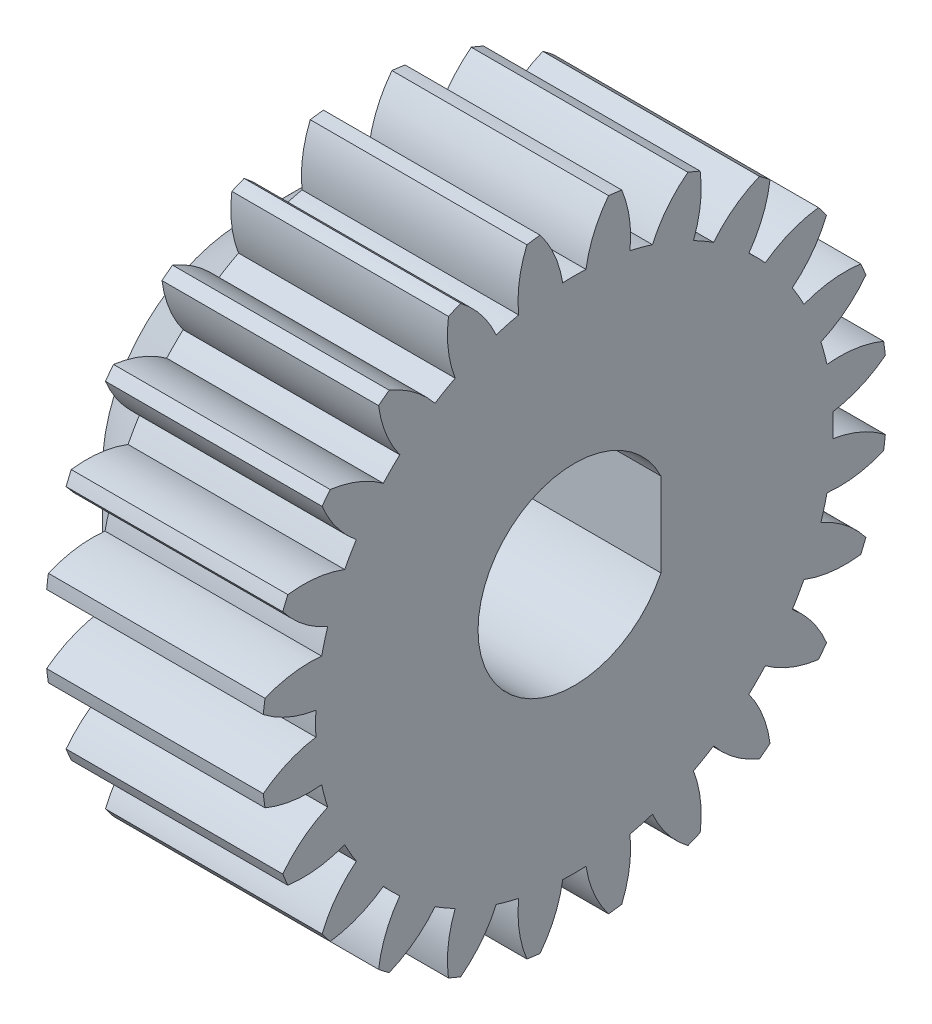
SolidWorks part; units mm, degrees
ref_plane "Plane1" through (0, 0, 0) normal (0, 0, 1) x (1, 0, 0)
ref_plane "Plane2" through (0, 0, 0) normal (0, 1, 0) x (1, 0, 0)
ref_plane "Plane3" through (0, 0, 0) normal (1, 0, 0) x (0, 0, -1)
sketch "HoldingSke" plane through (0, 0, 0) normal (0, 1, 0) x (1, 0, 0)
  line L0 (0, 0) -> (1.8271, -0.8135)
  line L1 (-15, 0) -> (100, 0) construction
  line L2 (0, 0) -> (-2.1039, 2.3779)
  line L3 (0, 0) -> (-11.863, 4.5341)
  line L4 (0, 0) -> (7.8894, 3.5126)
  line L5 (0, 0) -> (-46.8476, -17.4728)
  line L6 (0, 0) -> (-3.7303, -2.5169)
  line L7 (-2.1039, 2.3779) -> (8.6586, 51.2059)
  line L8 (-76.2, 54.61) -> (-75.7, 54.61)
  line L9 (-71.009, 38.7566) -> (-53.1078, 45.2721)
  line L10 (-76.2, 71.12) -> (104.1128, 71.12)
  line L11 (0, 0) -> (-4.5, 0)
  line L12 (-76.2, 101.6) -> (-76.181, 101.6)
  line L13 (24.9733, 27.94) -> (52.9518, 28.4284)
  line L14 (24.9733, 27.94) -> (24.9743, 27.94)
  line L15 (24.9733, 27.94) -> (100.4006, 29.5858)
  line L16 (-63.627, -0.5) -> (-12.827, -0.5)
  circle A0 centre (0, 0) radius 1.5
  circle A1 centre (0, 0) radius 5.374
  circle A2 centre (0, 0) radius 37.5
  circle A3 centre (0, 0) radius 1.5
  dimension "MHD" = 10.748
  dimension "Hub_dia" = 75
  dimension "Bore" = 3
  dimension "MBD" = 3
  dimension "Num_teeth" = 24
  dimension "Pitch" = 2
  dimension "Overall_len" = 50
  dimension "Show_teeth" = 24
  dimension "Thickness" = 4.5
  dimension "OAL" = 50.0001
  dimension "T_dim" = 0.5
  dimension "Ap" = 20
  dimension "H" = 19.05
  dimension "Pitch_radius" = 180.3128
  dimension "Width" = 4.5
  dimension "Backlash" = 0.019
  dimension "Addendum_fac" = 1
  dimension "Dedendum_fac" = 1.25
  dimension "Clearance_fac" = 0.25
  dimension "Dedendum_add" = 0.001
  dimension "Module" = 0.5
sketch "BasProSke" plane through (0, 0, 0) normal (0, 1, 0) x (1, 0, 0)
  line L0 (-10, 0) -> (60, 0) construction
  line L1 (0, 0) -> (0, 6.5)
  line L2 (0, 0) -> (4.5, 0)
  line L3 (4.5, 0) -> (4.5, 6.5)
  line L4 (4.5, 6.5) -> (0, 6.5)
  dimension "Thickness" = 4.5
  dimension "Diameter" = 13
revolve "Base-Revolve" add sketch "BasProSke" angle 360 about L0
sketch "TooCutSke" plane through (0, 0, 0) normal (1, 0, 0) x (0, 0, -1)
  line L1 (0, 0) -> (0, 107) construction
  line L2 (0, 0) -> (-0.4257, 5.9849) construction
  line L3 (0, 0) -> (-1.5635, 11.876) construction
  line L4 (-0.4257, 5.9849) -> (-0.7818, 5.938) construction
  arc A0 (0.2416, 5.3686) -> (-0.2416, 5.3686) centre (0, 0) ccw
  arc A1 (0.7297, 6.4845) -> (-0.7297, 6.4845) centre (0, 0) ccw
  circle A2 centre (0, 0) radius 6 construction
  circle A3 centre (0, 0) radius 5.6382 construction
  arc A4 (-0.2416, 5.3686) -> (-0.7297, 6.4845) centre (-2.6126, 4.9963) ccw
  arc A5 (0.7297, 6.4845) -> (0.2416, 5.3686) centre (2.6126, 4.9963) ccw
  dimension "Root_dia" = 10.748
  dimension "Overcut_dia" = 13.0508
  dimension "Pitch_dia" = 12
  dimension "Base_dia" = 11.2763
  dimension "Flank_rad" = 2.4
  dimension "Half_ang" = 7.5
  dimension "Half_CT" = 0.3592
extrude "ToothCut" cut sketch "TooCutSke" along normal through all
fillet "Breaks" [suppressed] radius 0.01
fillet "RootFillets" [suppressed] radius 0.126
pattern_circular "TeethCuts" count 24 every 15 about axis through (-10, 0, 0) along (1, 0, 0) of "ToothCut", "RootFillets", "Breaks"
sketch "HubNeaOneSke" plane through (0, 0, 0) normal (-1, 0, 0) x (0, 0, 1)
  circle A0 centre (0, 0) radius 5.374
  dimension "Diameter" = 10.748
extrude "HubNearOne" [suppressed] add sketch "HubNeaOneSke" along normal blind 45.5001
sketch "HubNeaBotSke" plane through (0, 0, 0) normal (-1, 0, 0) x (0, 0, 1)
  circle A0 centre (0, 0) radius 5.374
  dimension "Diameter" = 10.748
extrude "HubNearBoth" [suppressed] add sketch "HubNeaBotSke" along normal blind 22.75
ref_plane "FarPln" through (4.5, 0, 0) normal (1, 0, 0) x (0, 0, -1)
sketch "HubFarSke" plane through (4.5, 0, 0) normal (1, 0, 0) x (0, 0, -1)
  circle A0 centre (0, 0) radius 5.374
  dimension "Diameter" = 10.748
extrude "HubFar" [suppressed] add sketch "HubFarSke" along normal blind 22.75
sketch "BorSke" plane through (0, 0, 0) normal (1, 0, 0) x (0, 0, -1)
  circle A0 centre (0, 0) radius 1.5
  dimension "Diameter" = 3
extrude "Bore" cut sketch "BorSke" along normal mid plane 100.0001
sketch "KeySke" plane through (0, 0, 0) normal (1, 0, 0) x (0, 0, -1)
  line L0 (-0.6, 0) -> (-0.6, 2)
  line L1 (-0.6, 2) -> (0.6, 2)
  line L2 (0.6, 2) -> (0.6, 0)
  line L3 (0, 0) -> (0, 34) construction
  line L4 (-0.6, 0) -> (0.6, 0)
  dimension "Offset" = 2
  dimension "Width" = 1.2
extrude "Keyway" [suppressed] cut sketch "KeySke" along normal mid plane 100.0001
pattern_circular "Keyway2" [suppressed] count 2 every 90 about axis through (-10, 0, 0) along (1, 0, 0)
sketch "草图1" plane through (0, 0, 0) normal (0, 1, 0) x (1, 0, 0)
  line L0 (0, 0) -> (-2.33, 0)
  line L1 (-2.33, 0) -> (-2.33, 2.97)
  line L2 (-2.33, 2.97) -> (0, 5.3)
  line L3 (0, 0) -> (0, 5.3)
revolve "旋转1" add sketch "草图1" angle 360 about L0
sketch "草图2" plane through (4.5, 0, 0) normal (1, 0, 0) x (0, 0, -1)
  line L0 (1.8, -0.8718) -> (1.8, 0.8718)
  arc A0 (1.8, 0.8718) -> (1.8, -0.8718) centre (0, 0) ccw
  dimension "D1" = 1.8
extrude "切除-拉伸1" cut sketch "草图2" against normal up to next contours A0 L0
equation "' \"Module@HoldingSke\" = 6.35"
equation "' \"Num_teeth@HoldingSke\" = 12"
equation "' \"Ap@HoldingSke\" =  20"
equation "' \"Ap@HoldingSke\" = 20"
equation "' \"Width@HoldingSke\" = 0.5 * 25.4"
equation "' \"Hub_dia@HoldingSke\"= 1 * 25.4"
equation "' \"Hub_dia@HoldingSke\" = 1 * 25.4"
equation "' \"Overall_len@HoldingSke\" = 1.0 * 25.4"
equation "' \"Bore@HoldingSke\" = 0.75 * 25.4"
equation "' \"T_dim@HoldingSke\" = 0.1 * 25.4"
equation "' \"Width@KeySke\" = 0.25 * 25.4"
equation "' \"Show_teeth@HoldingSke\" = 13"
equation "' \"Backlash@HoldingSke\" = 0.009 * 25.4"
equation "' \"Addendum_fac@HoldingSke\" = 1.0"
equation "' \"Dedendum_fac@HoldingSke\" = 1.25"
equation "' \"Dedendum_add@HoldingSke\" = 0.00005 * 25.4"
equation "' \"Clearance_fac@HoldingSke\" = 0.25"
equation "\"Pitch@HoldingSke\" = 1 / \"Module@HoldingSke\""
equation "\"Overcut_dia@TooCutSke\" = (\"Num_teeth@HoldingSke\" + 2 * \"Addendum_fac@HoldingSke\") / \"Pitch@HoldingSke\" + 0.002 * 25.4"
equation "\"Pitch_dia@TooCutSke\" = \"Num_teeth@HoldingSke\" / \"Pitch@HoldingSke\""
equation "\"Base_dia@TooCutSke\" = \"Num_teeth@HoldingSke\" / \"Pitch@HoldingSke\" * cos((\"Ap@HoldingSke\"  * 3.14159265 / 180))"
equation "\"Root_dia@TooCutSke\" = (\"Num_teeth@HoldingSke\" + 2) / \"Pitch@HoldingSke\" - 2 * (\"Addendum_fac@HoldingSke\" + \"Dedendum_fac@HoldingSke\") / \"Pitch@HoldingSke\" - \"Dedendum_add@HoldingSke\" * 2"
equation "\"Half_ang@TooCutSke\" = 180 / \"Num_teeth@HoldingSke\""
equation "\"Half_CT@TooCutSke\" = \"Num_teeth@HoldingSke\" / \"Pitch@HoldingSke\" * sin((3.14159265 / 2 / \"Num_teeth@HoldingSke\")) / 2 - 7 * \"Backlash@HoldingSke\" / 4"
equation "\"Flank_rad@TooCutSke\" = \"Num_teeth@HoldingSke\" / \"Pitch@HoldingSke\" / 5"
equation "\"Radius@RootFillets\" = \"Clearance_fac@HoldingSke\" / \"Pitch@HoldingSke\" + \"Dedendum_add@HoldingSke\""
equation "\"Break_rad@Breaks\" = 0.02 / \"Pitch@HoldingSke\""
equation "\"Thickness@HoldingSke\" = \"Width@HoldingSke\""
equation "\"OAL@HoldingSke\" = \"Thickness@HoldingSke\""
equation "\"MHD@HoldingSke\" = (\"Num_teeth@HoldingSke\" + 2) / \"Pitch@HoldingSke\" - 2 * (\"Addendum_fac@HoldingSke\" + \"Dedendum_fac@HoldingSke\")  / \"Pitch@HoldingSke\" - \"Dedendum_add@HoldingSke\" * 2"
equation "\"MBD@HoldingSke\" = (\"Num_teeth@HoldingSke\" + 2) / \"Pitch@HoldingSke\" - 2 * (\"Addendum_fac@HoldingSke\" + \"Dedendum_fac@HoldingSke\")  / \"Pitch@HoldingSke\" - \"Dedendum_add@HoldingSke\" * 2 - 0.002 * 25.4"
equation "\"MHD@HoldingSke\" = ((sgn( \"MHD@HoldingSke\" - \"Hub_dia@HoldingSke\" )-1)*( \"MHD@HoldingSke\" - \"Hub_dia@HoldingSke\" ))/-2+ \"Hub_dia@HoldingSke\""
equation "\"MBD@HoldingSke\" = ((sgn( \"MBD@HoldingSke\" - \"Bore@HoldingSke\" )-1)*( \"MBD@HoldingSke\" - \"Bore@HoldingSke\" ))/-2+ \"Bore@HoldingSke\""
equation "\"OAL@HoldingSke\" = ((sgn( \"OAL@HoldingSke\" - \"Overall_len@HoldingSke\" )+1)*( \"OAL@HoldingSke\" - \"Overall_len@HoldingSke\" ))/2 + \"Overall_len@HoldingSke\" + 0.000002 * 25.4"
equation "\"Num_teeth@TeethCuts\" = int( \"Show_teeth@HoldingSke\" ) + 1"
equation "\"Num_teeth@TeethCuts\" = ((sgn( \"Num_teeth@TeethCuts\" - \"Num_teeth@HoldingSke\" )-1)*( \"Num_teeth@TeethCuts\" - \"Num_teeth@HoldingSke\" ))/-2+ \"Num_teeth@HoldingSke\""
equation "\"Num_teeth@TeethCuts\" = ((sgn( \"Num_teeth@TeethCuts\" - 2.0)+1)*( \"Num_teeth@TeethCuts\" - 2.0))/2 +2.0"
equation "\"Angle@TeethCuts\" = 360.0 / \"Num_teeth@HoldingSke\""
equation "\"Diameter@BasProSke\" = (\"Num_teeth@HoldingSke\" + 2 * \"Addendum_fac@HoldingSke\") / \"Pitch@HoldingSke\""
equation "\"Thickness@BasProSke\"  = \"Thickness@HoldingSke\""
equation "' \"Fillet_rad@BasProSke\" =  \"Thickness@HoldingSke\" * 0.05"
equation "' \"Fillet_rad@BasProSke\" = \"Thickness@HoldingSke\" * 0.05"
equation "\"MHD@HoldingSke\" = ((sgn( \"MHD@HoldingSke\" - \"Root_dia@TooCutSke\" )-1)*( \"MHD@HoldingSke\" - \"Root_dia@TooCutSke\" ))/-2+ \"Root_dia@TooCutSke\""
equation "\"Diameter@HubNeaOneSke\" = \"MHD@HoldingSke\""
equation "\"Length@HubNearOne\" = \"OAL@HoldingSke\" - \"Thickness@BasProSke\""
equation "\"Diameter@HubNeaBotSke\" = \"MHD@HoldingSke\""
equation "\"Length@HubNearBoth\" = ( \"OAL@HoldingSke\" - \"Thickness@BasProSke\" ) / 2.0"
equation "\"Thickness@FarPln\" = \"Thickness@BasProSke\""
equation "\"Diameter@HubFarSke\" = \"MHD@HoldingSke\""
equation "\"Length@HubFar\" = ( \"OAL@HoldingSke\" - \"Thickness@BasProSke\" ) / 2.0"
equation "\"Diameter@BorSke\" = \"MBD@HoldingSke\""
equation "\"D1@Bore\" = \"OAL@HoldingSke\" * 2.0"
equation "\"D1@Keyway\" = \"OAL@HoldingSke\" * 2.0"
equation "\"Offset@KeySke\" = \"T_dim@HoldingSke\" + \"MBD@HoldingSke\" / 2.0"
